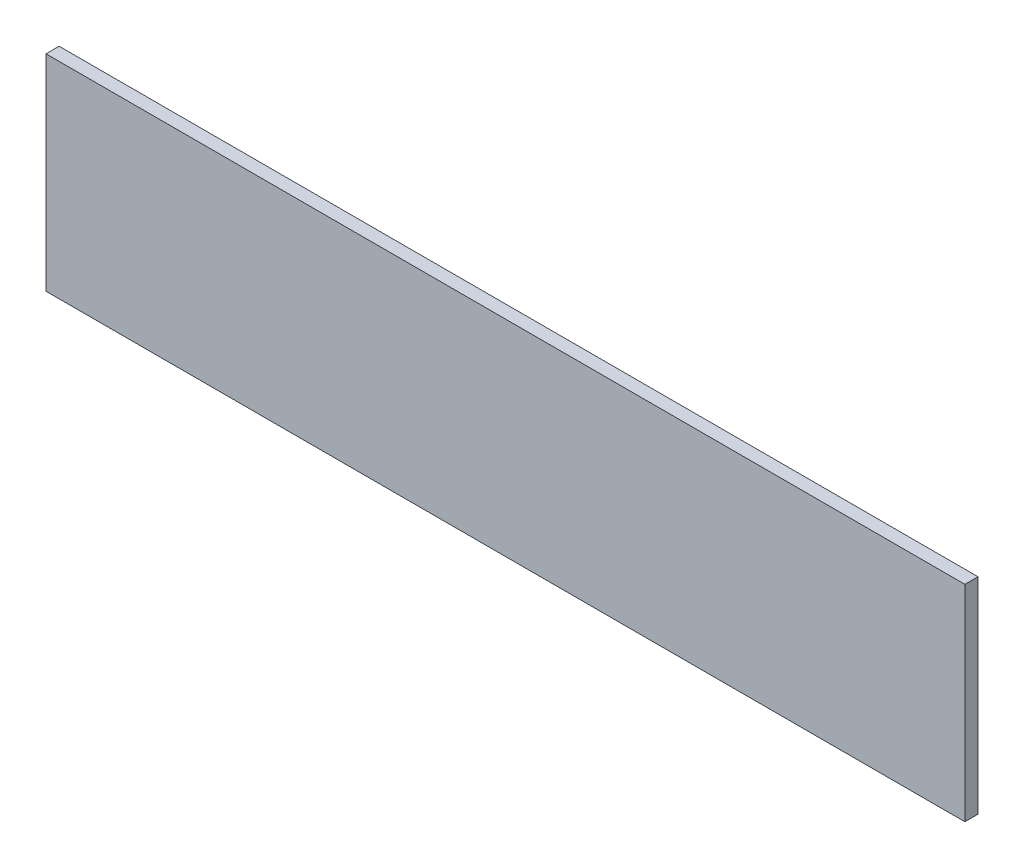
SolidWorks part; units mm, degrees
ref_plane "Front Plane" through (0, 0, 0) normal (0, 0, 1) x (1, 0, 0)
ref_plane "Top Plane" through (0, 0, 0) normal (0, 1, 0) x (1, 0, 0)
ref_plane "Right Plane" through (0, 0, 0) normal (1, 0, 0) x (0, 0, -1)
sketch "Sketch3" plane through (0, 0, 0) normal (0, 1, 0) x (1, 0, 0)
  line L0 (-178.5238, -1.0476) -> (31.4762, -1.0476)
  line L1 (31.4762, -1.0476) -> (31.4762, 1.9524)
  line L2 (31.4762, 1.9524) -> (-178.5238, 1.9524)
  line L3 (-178.5238, 1.9524) -> (-178.5238, -1.0476)
  dimension "D1" = 3
  dimension "D2" = 3
  dimension "D3" = 210
extrude "Boss-Extrude1" add sketch "Sketch3" along normal blind 47 contours L3 L0 L1 L2
